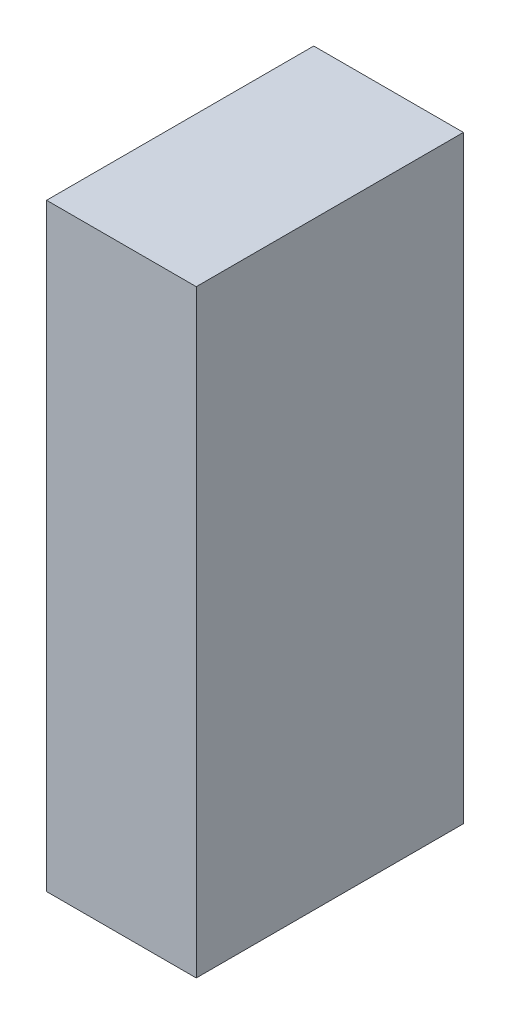
SolidWorks part; units mm, degrees
ref_plane "Front Plane" through (0, 0, 0) normal (0, 0, 1) x (1, 0, 0)
ref_plane "Top Plane" through (0, 0, 0) normal (0, 1, 0) x (1, 0, 0)
ref_plane "Right Plane" through (0, 0, 0) normal (1, 0, 0) x (0, 0, -1)
sketch "Sketch1" plane through (0, 0, 0) normal (0, 0, 1) x (1, 0, 0)
  line L1 (0, 0) -> (25.4, 0)
  line L2 (0, 0) -> (0, 101.6)
  line L3 (0, 101.6) -> (25.4, 101.6)
  line L4 (25.4, 0) -> (25.4, 101.6)
  dimension "D1" = 25.4
  dimension "D2" = 101.6
extrude "Boss-Extrude1" add sketch "Sketch1" along normal up to surface (45.339 mm away)
ref_plane "Plane1" through (12.7, 0, 0) normal (-1, 0, 0) x (0, 0, 1)
